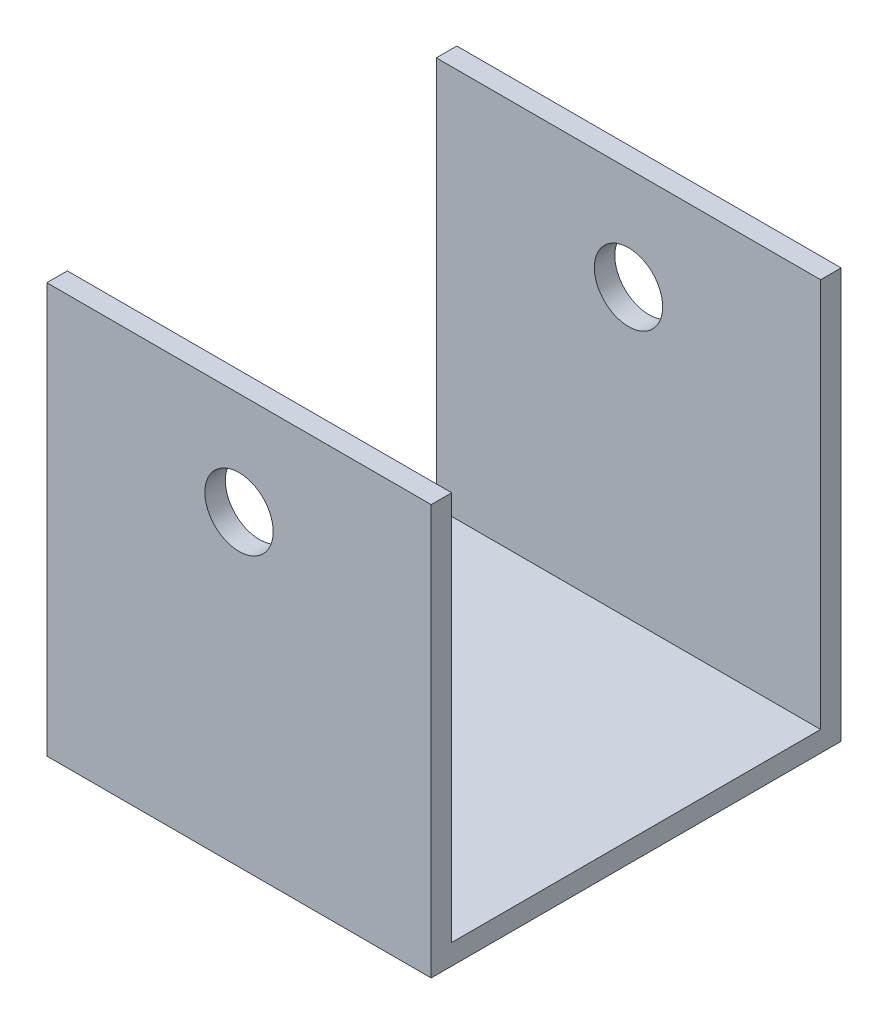
SolidWorks part; units mm, degrees
ref_plane "Front Plane" through (0, 0, 0) normal (0, 0, 1) x (1, 0, 0)
ref_plane "Top Plane" through (0, 0, 0) normal (0, 1, 0) x (1, 0, 0)
ref_plane "Right Plane" through (0, 0, 0) normal (1, 0, 0) x (0, 0, -1)
sketch "Sketch1" plane through (0, 0, 0) normal (0, 0, 1) x (1, 0, 0)
  line L1 (-35.7188, 38.1) -> (0, 38.1)
  line L2 (-35.7188, 38.1) -> (-35.7188, 0)
  line L3 (-35.7188, 0) -> (0, 0)
  line L4 (0, 38.1) -> (0, 0)
  dimension "D1" = 38.1
  dimension "D2" = 35.7188
extrude "Boss-Extrude1" add sketch "Sketch1" along normal blind 38.1
sketch "Sketch2" plane through (-35.7188, 0, 0) normal (-1, 0, 0) x (0, 0, 1)
  line L0 (38.1, 38.1) -> (0, 38.1) construction
  line L1 (1.905, 38.1) -> (36.195, 38.1)
  line L2 (1.905, 38.1) -> (1.905, 1.905)
  line L3 (1.905, 1.905) -> (36.195, 1.905)
  line L4 (36.195, 38.1) -> (36.195, 1.905)
  line L5 (38.1, 38.1) -> (38.1, 0) construction
  line L6 (0, 38.1) -> (0, 0) construction
  line L7 (38.1, 0) -> (0, 0) construction
  dimension "D1" = 1.905
  dimension "D2" = 1.905
  dimension "D3" = 1.905
extrude "Cut-Extrude1" cut sketch "Sketch2" against normal through all
sketch "Sketch3" plane through (0, 0, 36.195) normal (0, 0, -1) x (-1, 0, 0)
  line L0 (35.7188, 38.1) -> (35.7188, 0) construction
  line L1 (35.7188, 0) -> (0, 0) construction
  circle A0 centre (17.8594, 28.575) radius 3.175
  dimension "D1" = 17.8594
  dimension "D3" = 6.35
  dimension "D2" = 28.575
extrude "Cut-Extrude2" cut sketch "Sketch3" against normal through all both and the other way through all
